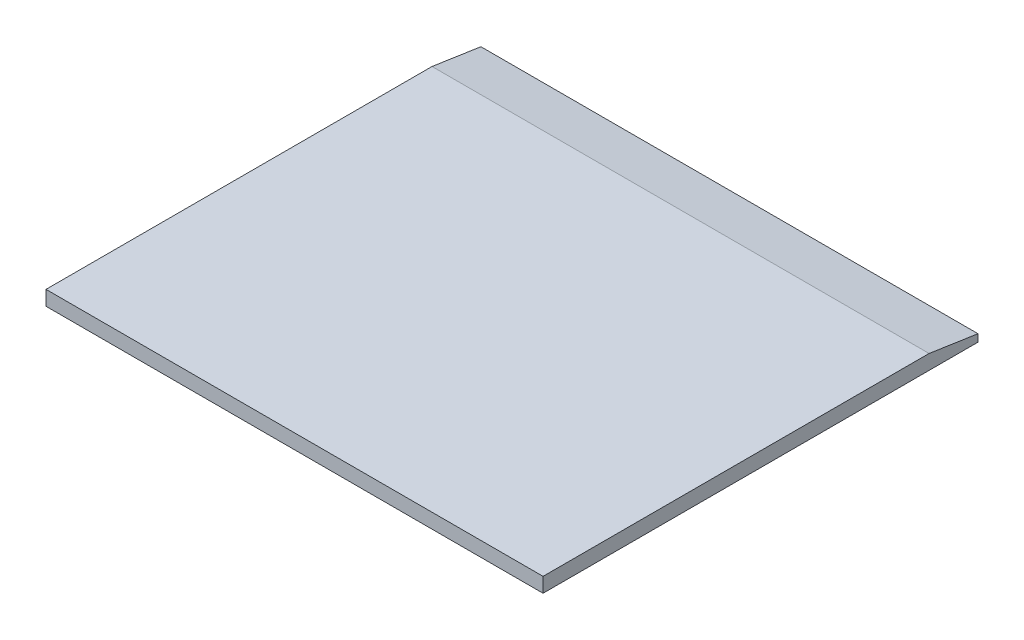
SolidWorks part; units mm, degrees
ref_plane "Front Plane" through (0, 0, 0) normal (0, 0, 1) x (1, 0, 0)
ref_plane "Top Plane" through (0, 0, 0) normal (0, 1, 0) x (1, 0, 0)
ref_plane "Right Plane" through (0, 0, 0) normal (1, 0, 0) x (0, 0, -1)
sketch "Croquis1" plane through (0, 0, 0) normal (0, 1, 0) x (1, 0, 0)
  line L1 (0, 0) -> (101.6, 0)
  line L2 (0, 0) -> (0, 88.9)
  line L3 (0, 88.9) -> (101.6, 88.9)
  line L4 (101.6, 0) -> (101.6, 88.9)
  dimension "D1" = 101.6
  dimension "D2" = 88.9
extrude "Saliente-Extruir1" add sketch "Croquis1" along normal blind 3
sketch "Croquis2" plane through (101.6, 0, 0) normal (1, 0, 0) x (0, 0, -1)
  line L0 (88.9, 3) -> (88.9, 1.5)
  line L1 (88.9, 3) -> (88.9, 0) construction
  line L2 (88.9, 1.5) -> (78.9, 3)
  line L3 (0, 3) -> (88.9, 3) construction
  line L4 (78.9, 3) -> (78.9, 5.8061)
  line L5 (78.9, 5.8061) -> (88.9, 5.8061)
  line L6 (88.9, 5.8061) -> (88.9, 3)
  dimension "D1" = 10
extrude "Cortar-Extruir1" cut sketch "Croquis2" against normal through all and the other way through all
